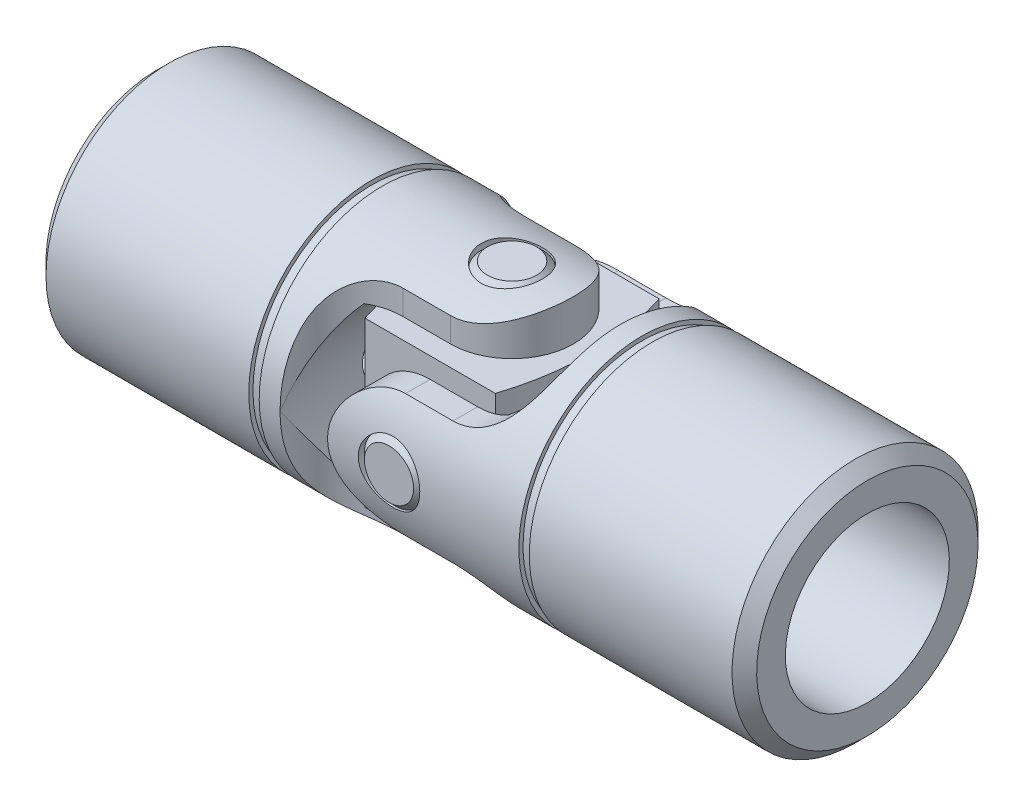
SolidWorks part; units mm, degrees
ref_plane "Front Plane" through (0, 0, 0) normal (0, 0, 1) x (1, 0, 0)
ref_plane "Top Plane" through (0, 0, 0) normal (0, 1, 0) x (1, 0, 0)
ref_plane "Right Plane" through (0, 0, 0) normal (1, 0, 0) x (0, 0, -1)
sketch "Sketch0" plane through (0, 0, 0) normal (0, 1, 0) x (1, 0, 0)
  line L0 (-41.275, 0) -> (41.275, 0) construction
  line L1 (-41.275, 14.2875) -> (-41.275, -14.2875) construction
  line L2 (-17.4625, 9.525) -> (-17.4625, -9.525) construction
  line L3 (-17.4625, 9.525) -> (-7.9375, 0) construction
  line L4 (-7.9375, 0) -> (-17.4625, -9.525) construction
  line L5 (-12.7, 4.7625) -> (-12.7, -4.7625) construction
  point P7 (-17.4625, 0)
  point P8 (0, 0)
  point P12 (-12.7, 0)
sketch "Sketch1" plane through (0, 0, 0) normal (0, 1, 0) x (1, 0, 0)
  line L0 (-41.275, 14.2875) -> (-16.2917, 14.2875)
  line L1 (7.1437, 14.2875) -> (7.1437, 0)
  line L2 (7.1437, 0) -> (-41.275, 0)
  line L3 (-41.275, 0) -> (-41.275, 14.2875)
  line L4 (-41.275, 14.2875) -> (-41.275, -14.2875) construction
  line L5 (-41.275, 0) -> (41.275, 0) construction
  line L6 (-15.0812, 14.2875) -> (7.1437, 14.2875)
  line L7 (-15.0812, 4.7625) -> (-15.0812, 13.8033) construction
  line L8 (-16.2917, 14.2875) -> (-16.2917, 13.8033)
  line L9 (-16.2917, 13.8033) -> (-15.0812, 13.8033)
  line L10 (-15.0812, 14.2875) -> (-15.0812, 13.8033)
  line L11 (0, 0) -> (14.2875, 0) construction
  line L12 (-12.7, 4.7625) -> (-17.4625, 4.7625) construction
  line L13 (-17.4625, 9.525) -> (-17.4625, -9.525) construction
  circle A0 centre (0, 0) radius 14.2875 construction
  dimension "D1" = 1.2105
  dimension "D2" = 0.4842
  dimension "D3" = 48.4187
revolve "Revolve1" add sketch "Sketch1" angle 360 about L0
chamfer "Chamfer1" distance 1.4287 angle 45 1 edges at (-41.275, 0, 14.2875)
sketch "Sketch2" plane through (0, 0, 0) normal (0, 1, 0) x (1, 0, 0)
  line L0 (-15.0812, 14.2875) -> (-12.6603, 14.2875) construction
  line L1 (-15.0812, 14.2875) -> (7.1437, 14.2875) construction
  line L2 (7.1437, 14.2875) -> (-15.0812, 14.2875) construction
  line L4 (-41.275, 0) -> (7.1437, 0) construction
  line L5 (-12.6603, 14.2875) -> (14.2875, 14.2875)
  line L6 (14.2875, 14.2875) -> (14.2875, -14.2875)
  line L7 (14.2875, -14.2875) -> (-12.6603, -14.2875)
  line L8 (0, 7.1437) -> (0, 0) construction
  line L9 (0, 7.1437) -> (-5.5166, 7.1437)
  line L10 (-12.6603, 14.2875) -> (-12.6603, -14.2875) construction
  line L11 (0, -7.1437) -> (-5.5166, -7.1437)
  arc A0 (-12.6603, 14.2875) -> (-5.5166, 7.1437) centre (-5.5166, 14.2875) ccw
  arc A1 (0, -7.1437) -> (0, 7.1437) centre (0, 0) ccw
  arc A2 (-5.5166, -7.1437) -> (-12.6603, -14.2875) centre (-5.5166, -14.2875) ccw
  dimension "D1" = 14.2875
  dimension "D2" = 2.4209
extrude "Extrude1" cut sketch "Sketch2" against normal through all and the other way through all
sketch "Sketch3" plane through (0, 0, 0) normal (0, 0, 1) x (1, 0, 0)
  line L0 (-9.0884, 9.5155) -> (-12.6603, 5.9436) construction
  line L1 (-9.0884, 9.5155) -> (14.2875, 9.5155)
  line L2 (-12.6603, 5.9436) -> (-12.6603, -5.9436) construction
  line L3 (-9.0884, -9.5155) -> (14.2875, -9.5155)
  line L4 (14.2875, 9.5155) -> (14.2875, -9.5155)
  line L5 (-12.6603, -5.9436) -> (-9.0884, -9.5155) construction
  line L6 (-12.6603, 0) -> (-5.5166, 0) construction
  line L7 (-5.5166, -12.3733) -> (-5.5166, 12.3733) construction
  line L8 (14.2875, 0) -> (-12.6603, 0) construction
  line L9 (-9.0884, 0) -> (-9.0884, 9.5155) construction
  arc A0 (-9.0884, 9.5155) -> (-9.0884, -9.5155) centre (1.8002, 0) ccw
  dimension "D1" = 19.031
extrude "Extrude3" cut sketch "Sketch3" against normal through all and the other way through all
sketch "Sketch4" plane through (-41.275, 0, 0) normal (-1, 0, 0) x (0, 0, 1)
  circle A0 centre (0, 0) radius 9.525
extrude "Extrude4" cut sketch "Sketch4" against normal up to vertex (23.8125 mm away) up to point (-17.4625, 0, -9.525)
sketch "Sketch5" plane through (-17.4625, 0, 0) normal (-1, 0, 0) x (0, 0, 1)
  circle A0 centre (0, 0) radius 9.525 construction
  circle A1 centre (0, 0) radius 9.525
extrude "Extrude5" cut sketch "Sketch5" against normal through all draft 45
sketch "Sketch6" plane through (0, 0, 0) normal (0, 1, 0) x (1, 0, 0)
  line L0 (-41.275, 0) -> (41.275, 0) construction
  line L1 (7.1437, 0) -> (3.5719, 0) construction
  line L2 (3.5719, 0) -> (0, 0) construction
  circle A0 centre (0, 0) radius 3.5719
  arc A1 (0, -7.1437) -> (0, 7.1437) centre (0, 0) ccw construction
  dimension "D1" = 7.1437
extrude "Extrude6" cut sketch "Sketch6" against normal through all and the other way through all
mirror "Mirror1" about plane through (0, 0, 0) normal (1, 0, 0) of bodies 109 122
move or copy body "Body-Move/Copy1" bodies to move or copy 110 copy no rotation origin (0, 0, 0) rotation axis (1, 0, 0) rotation angle 90
sketch "Sketch18" plane through (0, 0, 0) normal (0, 1, 0) x (1, 0, 0)
  line L0 (-47.625, -9.525) -> (-17.4625, -9.525)
  line L3 (-47.625, 9.525) -> (-17.4625, 9.525)
  line L4 (-17.4625, 9.525) -> (-17.4625, -9.525)
  line L5 (17.4625, 9.525) -> (17.4625, -9.525)
  line L6 (17.4625, -9.525) -> (41.275, -9.525)
  line L7 (17.4625, 9.525) -> (41.275, 9.525)
  line L8 (0, 0) -> (17.4625, 0) construction
  line L9 (41.275, -12.8588) -> (41.275, 12.8588) construction
  line L11 (-17.4625, -9.525) -> (-17.4625, 9.525) construction
sketch "Sketch10" plane through (0, 0, 0) normal (0, 0, 1) x (1, 0, 0)
  line L0 (-9.0884, 9.5155) -> (9.0884, -9.5155) construction
  line L1 (-9.0884, 9.5155) -> (9.0884, 9.5155)
  line L2 (-9.0884, 9.5155) -> (-9.0884, -9.5155)
  line L3 (-9.0884, -9.5155) -> (9.0884, -9.5155)
  line L4 (9.0884, 9.5155) -> (9.0884, -9.5155)
  line L5 (0, 9.5155) -> (7.1437, 9.5155) construction
extrude "Extrude10" add sketch "Sketch10" against normal up to surface and the other way up to surface separate body up to face at (-3.5719, 0, -9.5155) other way up to face at (3.5719, 0, 9.5155)
sketch "Sketch20" plane through (0, 9.5155, 0) normal (0, 1, 0) x (1, 0, 0)
  line L4 (9.0884, 9.5155) -> (-9.0884, 9.5155) construction
  line L5 (9.0884, -9.5155) -> (-9.0884, -9.5155) construction
  line L6 (-9.0884, 9.5155) -> (-9.0884, -9.5155) construction
  line L7 (9.0884, 9.5155) -> (9.0884, -9.5155) construction
  line L8 (10.1044, -10.5315) -> (10.1044, 10.5315)
  line L9 (10.1044, 10.5315) -> (-10.1044, 10.5315)
  line L10 (-10.1044, 10.5315) -> (-10.1044, -10.5315)
  line L11 (-10.1044, -10.5315) -> (10.1044, -10.5315)
  line L12 (10.1044, -10.5315) -> (10.1044, 10.5315)
  line L13 (10.1044, 10.5315) -> (7.5737, 10.5315)
  line L14 (-10.1044, 10.5315) -> (-10.1044, -10.5315)
  line L15 (-10.1044, -10.5315) -> (-7.5737, -10.5315)
  line L16 (-7.5737, 9.5155) -> (-7.5737, 10.5315)
  line L17 (7.5737, 9.5155) -> (7.5737, 10.5315)
  line L18 (7.5737, -9.5155) -> (7.5737, -10.5315)
  line L19 (-7.5737, -9.5155) -> (-7.5737, -10.5315)
  line L20 (-7.5737, 10.5315) -> (-10.1044, 10.5315)
  line L21 (7.5737, -10.5315) -> (10.1044, -10.5315)
  line L22 (-41.275, 0) -> (7.1437, 0) construction
  line L23 (9.0884, 9.5155) -> (-9.0884, 9.5155) construction
  arc A0 (7.5737, 9.5155) -> (7.5737, -9.5155) centre (-21.5567, 0) cw
  arc A1 (-7.5737, 9.5155) -> (-7.5737, -9.5155) centre (21.5567, 0) ccw
  dimension "D2" = 18.1769
  dimension "D3" = 1.5147
  dimension "D1" = 1.016
extrude "Cut-Extrude2" cut sketch "Sketch20" against normal through all
sketch "Sketch13" plane through (0, 0, 0) normal (0, 1, 0) x (1, 0, 0)
  circle A0 centre (0, 0) radius 3.5719 construction
  circle A1 centre (0, 0) radius 3.5719
extrude "Extrude13" cut sketch "Sketch13" against normal through all and the other way through all
sketch "Sketch14" plane through (0, 0, 0) normal (0, 1, 0) x (1, 0, 0)
  circle A1 centre (0, 0) radius 3.5719
  circle A2 centre (0, 0) radius 3.5719
  dimension "D1" = 0
extrude "Extrude14" add sketch "Sketch14" along normal mid plane 28.575 separate body
sketch "Sketch15" plane through (0, 0, 0) normal (0, 0, 1) x (1, 0, 0)
  circle A0 centre (0, 0) radius 3.5719 construction
  circle A1 centre (0, 0) radius 3.5719
extrude "Extrude15" cut sketch "Sketch15" against normal through all and the other way through all
sketch "Sketch16" plane through (0, 0, 0) normal (0, 0, 1) x (1, 0, 0)
  circle A1 centre (0, 0) radius 3.5719
  circle A2 centre (0, 0) radius 3.5719
  dimension "D1" = 0
extrude "Extrude16" add sketch "Sketch16" along normal mid plane 28.575
chamfer "Chamfer3" distance 0.7144 angle 45 4 edges at (0, -14.2875, 3.5719) (0, 14.2875, 3.5719) (3.5719, 0, 14.2875) (3.5719, 0, -14.2875)
move or copy body "Body-Move/Copy2" [suppressed] bodies to move or copy 111 copy no rotation origin (0, 0, 0) rotation axis (0, 0, -1) rotation angle 15
equation "\"D2@Sketch3\" = \"D1@Sketch3\" / 4"
equation "\"D1@Extrude14\" = \"OD@Sketch0\""
equation "\"D1@Extrude16\" = \"D1@Extrude14\""
equation "\"D1@Sketch3\" = \"OD@Sketch0\"*.666"
equation "\"D1@Sketch1\" = \"D3@Sketch1\"*.025"
equation "\"D2@Sketch1\" = \"D1@Sketch1\"/2.5"
equation "\"D1@Chamfer1\" = \"OD@Sketch0\"/20"
equation "\"D1@Chamfer3\" = \"D1@Chamfer1\"*.50"
equation "\"D2@Sketch2\" = \"D1@Sketch1\"*2"
equation "\"D3@Sketch20\" = \"D2@Sketch20\"/12"
